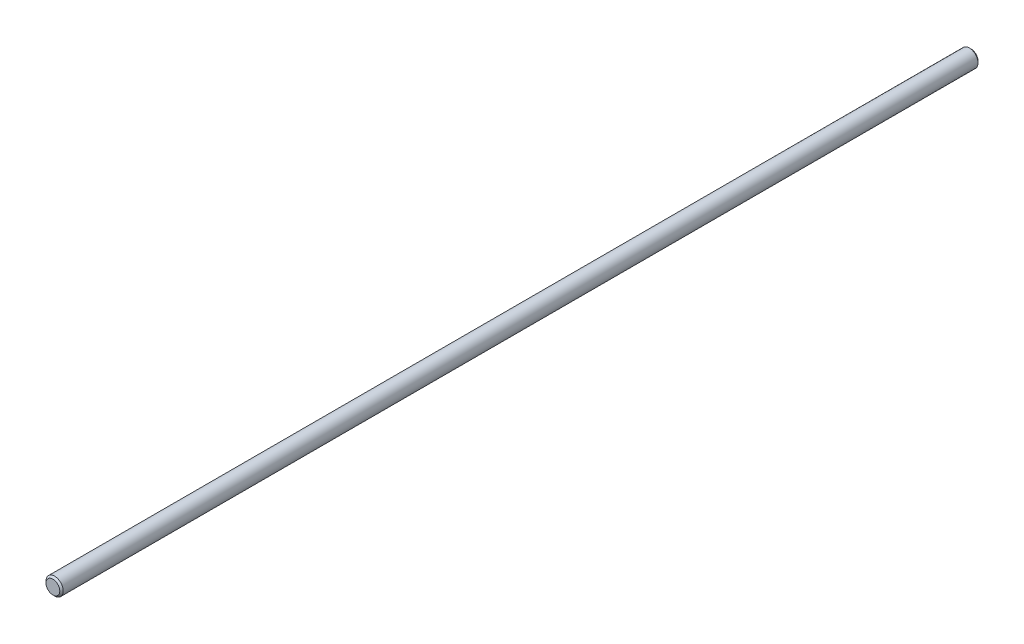
SolidWorks part; units mm, degrees
ref_plane "Front" through (0, 0, 0) normal (0, 0, 1) x (1, 0, 0)
ref_plane "Top" through (0, 0, 0) normal (0, 1, 0) x (1, 0, 0)
ref_plane "Right" through (0, 0, 0) normal (1, 0, 0) x (0, 0, -1)
sketch "Sketch1" plane through (0, 0, 0) normal (0, 0, 1) x (1, 0, 0)
  circle A0 centre (0, 0) radius 3
  dimension "D1" = 6
extrude "Extrude1" add sketch "Sketch1" along normal mid plane 320
chamfer "Chamfer1" distance 0.6 angle 45 2 edges at (3, 0, -160) (3, 0, 160)
equation "\"D1@Chamfer1\" = \"D1@Sketch1\" * .1"
